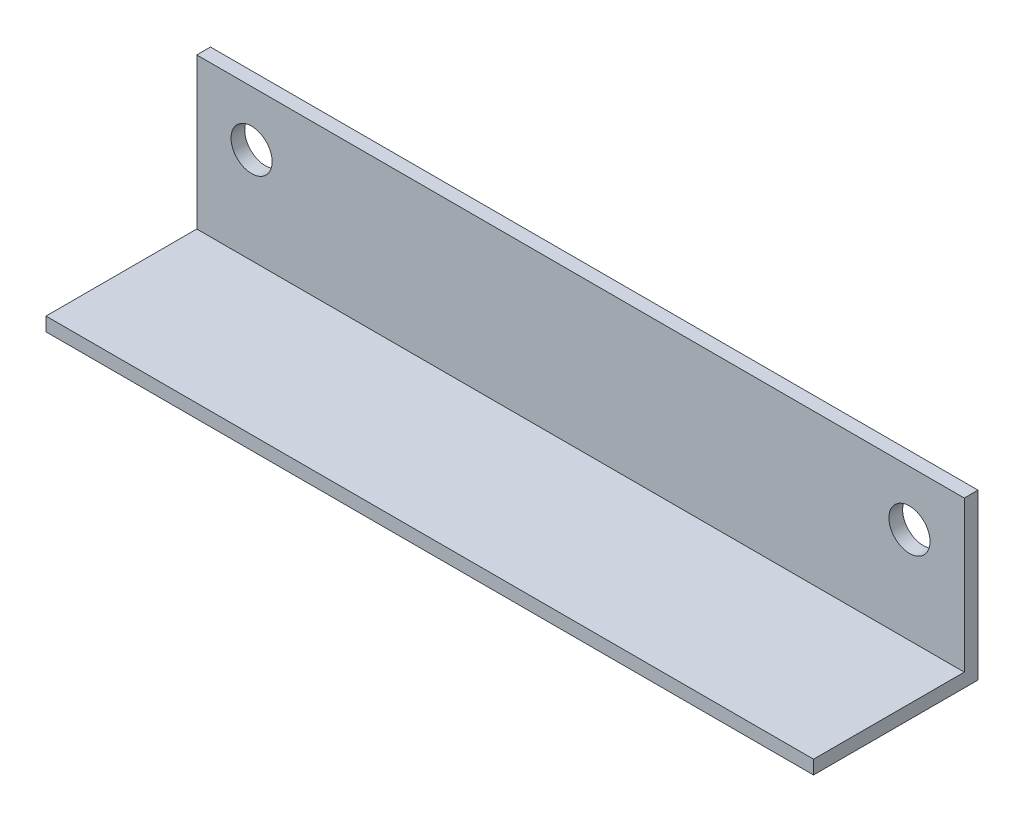
SolidWorks part; units mm, degrees
material "Plain Carbon Steel"
ref_plane "Front Plane" through (0, 0, 0) normal (0, 0, 1) x (1, 0, 0)
ref_plane "Top Plane" through (0, 0, 0) normal (0, 1, 0) x (1, 0, 0)
ref_plane "Right Plane" through (0, 0, 0) normal (1, 0, 0) x (0, 0, -1)
sketch "Sketch1" plane through (0, 0, 0) normal (1, 0, 0) x (0, 0, -1)
  line L0 (-38.1, 0) -> (0, 0)
  line L1 (55, 0) -> (-55, 0) construction
  line L2 (0, 0) -> (0, 38.1)
  line L3 (0, 55) -> (0, -55) construction
  dimension "D1" = 38.1
extrude "Extrude-Thin1" add sketch "Sketch1" along normal mid plane 177.8 thin thin type one direction reverse wall 3.175
sketch "Sketch2" plane through (0, 0, 0) normal (0, 0, -1) x (-1, 0, 0)
  line L0 (-88.9, 38.1) -> (88.9, 38.1) construction
  line L3 (0, 20.955) -> (0, -20.955) construction
  circle A0 centre (-76.2, 25.4) radius 4.7625
  circle A1 centre (76.2, 25.4) radius 4.7625
  point P4 (0, 0)
  dimension "D1" = 12.7
  dimension "D4" = 9.525
  dimension "D2" = 76.2
  dimension "D3" = 76.2
extrude "Cut-Extrude1" cut sketch "Sketch2" against normal up to next
